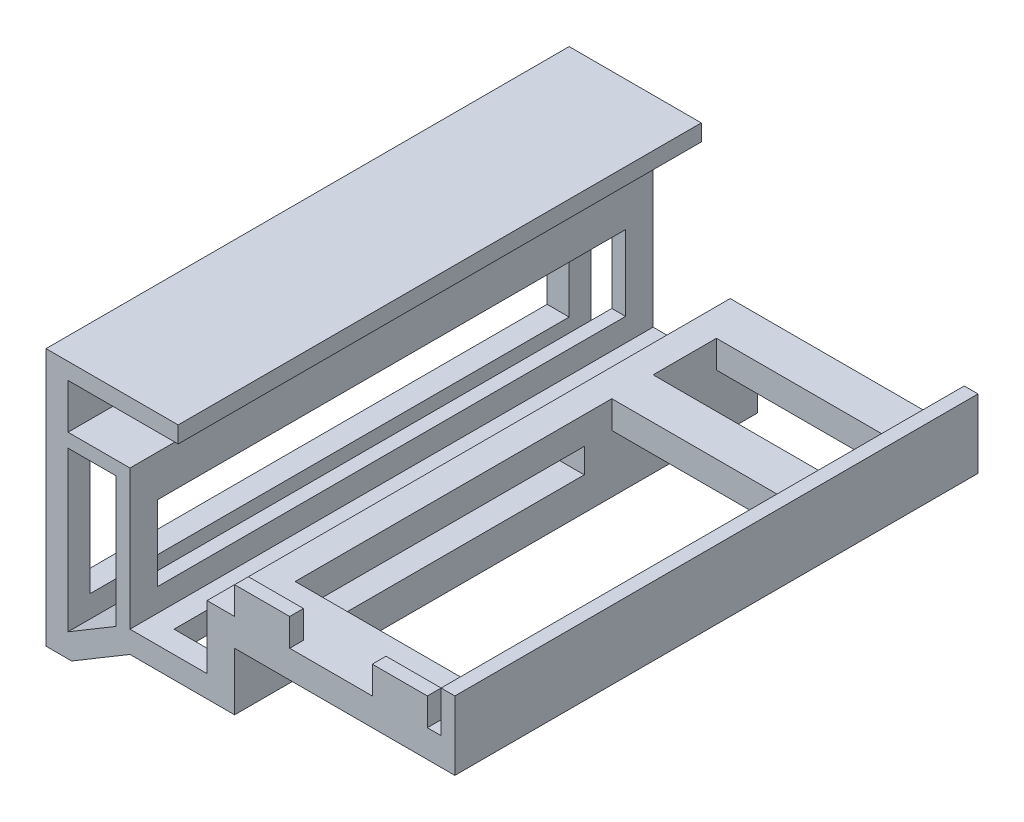
SolidWorks part; units mm, degrees
ref_plane "前视基准面" through (0, 0, 0) normal (0, 0, 1) x (1, 0, 0)
ref_plane "上视基准面" through (0, 0, 0) normal (0, 1, 0) x (1, 0, 0)
ref_plane "右视基准面" through (0, 0, 0) normal (1, 0, 0) x (0, 0, -1)
other "Configuration Table"
sketch "草图1" plane through (0, 0, 0) normal (0, 0, 1) x (1, 0, 0)
  line L0 (0, 0) -> (-22.5, 0)
  line L1 (-22.5, 0) -> (-22.5, 16.3)
  line L2 (-22.5, 16.3) -> (17.5, 16.3)
  line L3 (17.5, 16.3) -> (17.5, 22.3)
  line L4 (17.5, 22.3) -> (-30.5, 22.3)
  line L5 (-30.5, 22.3) -> (-30.5, -71.3085)
  line L6 (-30.5, -71.3085) -> (-21.1866, -71.3085)
  line L14 (113, -27.7) -> (28, -27.7)
  line L15 (28, -27.7) -> (28, -50.7)
  line L16 (28, -50.7) -> (0, -50.7)
  line L17 (0, -50.7) -> (0, 0)
  line L21 (118, -37.7) -> (38, -37.7)
  line L22 (38, -37.7) -> (38, -58.6513)
  line L23 (38, -58.6513) -> (0, -58.6513)
  line L24 (0, -58.6513) -> (-21.1866, -71.3085)
  line L26 (118, -37.7) -> (118, -12.7)
  line L27 (118, -12.7) -> (113, -12.7)
  line L28 (113, -12.7) -> (113, -27.7)
  dimension "D1" = 8
  dimension "D2" = 6
  dimension "D3" = 40
  dimension "D4" = 16.3
  dimension "D5" = 28
  dimension "D6" = 22.5
  dimension "D7" = 50.7
  dimension "D8" = 23
  dimension "D9" = 10
  dimension "D10" = 10
  dimension "D11" = 85
  dimension "D12" = 5
  dimension "D13" = 25
extrude "凸台-拉伸1" add sketch "草图1" along normal blind 190 contours L5 L6 L24 L23 L22 L21 L26 L27 L28 L14 L15 L16 L17 L0 L1 L2 L3 L4
sketch "草图2" plane through (0, 0, 190) normal (0, 0, 1) x (1, 0, 0)
  line L0 (-22.5, -5) -> (-22.5, -62.7742)
  line L1 (-22.5, -62.7742) -> (-5, -52.3194)
  line L2 (-5, -52.3194) -> (-5, -5)
  line L3 (-5, -5) -> (-22.5, -5)
  line L18 (17.5, 22.3) -> (-30.5, 22.3)
  line L19 (-30.5, 22.3) -> (-30.5, -71.3085)
  line L20 (-30.5, -71.3085) -> (-21.1866, -71.3085)
  line L21 (-21.1866, -71.3085) -> (0, -58.6513)
  line L22 (0, -58.6513) -> (38, -58.6513)
  line L23 (38, -58.6513) -> (38, -37.7)
  line L24 (38, -37.7) -> (118, -37.7)
  line L25 (118, -37.7) -> (118, -12.7)
  line L26 (118, -12.7) -> (113, -12.7)
  line L27 (113, -12.7) -> (113, -27.7)
  line L28 (113, -27.7) -> (28, -27.7)
  line L29 (28, -27.7) -> (28, -50.7)
  line L30 (28, -50.7) -> (0, -50.7)
  line L31 (0, -50.7) -> (0, 0)
  line L32 (0, 0) -> (-22.5, 0)
  line L33 (-22.5, 0) -> (-22.5, 16.3)
  line L34 (-22.5, 16.3) -> (17.5, 16.3)
  line L35 (17.5, 16.3) -> (17.5, 22.3)
  line L36 (17.5, 22.3) -> (-30.5, 22.3) construction
  line L37 (-30.5, 22.3) -> (-30.5, -71.3085) construction
  line L38 (-30.5, -71.3085) -> (-21.1866, -71.3085) construction
  line L39 (-21.1866, -71.3085) -> (0, -58.6513) construction
  line L40 (0, -58.6513) -> (38, -58.6513) construction
  line L41 (38, -58.6513) -> (38, -37.7) construction
  line L42 (38, -37.7) -> (118, -37.7) construction
  line L43 (118, -37.7) -> (118, -12.7) construction
  line L44 (118, -12.7) -> (113, -12.7) construction
  line L45 (113, -12.7) -> (113, -27.7) construction
  line L46 (113, -27.7) -> (28, -27.7) construction
  line L47 (28, -27.7) -> (28, -50.7) construction
  line L48 (28, -50.7) -> (0, -50.7) construction
  line L49 (0, -50.7) -> (0, 0) construction
  line L50 (0, 0) -> (-22.5, 0) construction
  line L51 (-22.5, 0) -> (-22.5, 16.3) construction
  line L52 (-22.5, 16.3) -> (17.5, 16.3) construction
  line L53 (17.5, 16.3) -> (17.5, 22.3) construction
  point P6 (-11.25, 0)
  dimension "D2" = 8
  dimension "D3" = 5
  dimension "D4" = 5
  dimension "D5" = 8
  dimension "D1" = 0
extrude "切除-拉伸1" cut sketch "草图2" against normal through all contours L3 L0 L1 L2
sketch "草图4" plane through (0, -27.7, 0) normal (0, 1, 0) x (1, 0, 0)
  line L0 (38, -15) -> (113, -15)
  line L1 (113, -15) -> (113, -38)
  line L2 (113, -38) -> (38, -38)
  line L4 (113, 0) -> (28, 0)
  line L5 (28, 0) -> (28, -190)
  line L6 (28, -190) -> (113, -190)
  line L7 (113, -190) -> (113, 0)
  line L8 (113, 0) -> (28, 0) construction
  line L9 (28, 0) -> (28, -190) construction
  line L10 (28, -190) -> (113, -190) construction
  line L11 (113, -190) -> (113, 0) construction
  line L12 (38, -190) -> (38, 0) construction
  line L13 (38, -190) -> (38, 0) construction
  line L14 (38, -15) -> (38, -38)
  dimension "D2" = 15
  dimension "D3" = 23
  dimension "D1" = 0
extrude "切除-拉伸2" cut sketch "草图4" against normal through all contours L0 L1 L2 L14
sketch "草图6" plane through (0, -27.7, 0) normal (0, 1, 0) x (1, 0, 0)
  line L0 (38, -53) -> (38, -168)
  line L1 (38, -168) -> (113, -168)
  line L2 (113, -168) -> (113, -53)
  line L3 (113, -53) -> (38, -53)
  line L8 (38, -15) -> (113, -15)
  line L9 (113, -15) -> (113, 0)
  line L10 (113, 0) -> (28, 0)
  line L11 (28, 0) -> (28, -190)
  line L12 (28, -190) -> (113, -190)
  line L13 (113, -190) -> (113, -38)
  line L14 (113, -38) -> (38, -38)
  line L15 (38, -38) -> (38, -15)
  line L16 (38, -15) -> (113, -15) construction
  line L17 (113, -15) -> (113, 0) construction
  line L18 (113, 0) -> (28, 0) construction
  line L19 (28, 0) -> (28, -190) construction
  line L20 (28, -190) -> (113, -190) construction
  line L21 (113, -190) -> (113, -38) construction
  line L22 (113, -38) -> (38, -38) construction
  line L23 (38, -38) -> (38, -15) construction
  dimension "D2" = 15
  dimension "D3" = 115
  dimension "D1" = 0
extrude "切除-拉伸3" cut sketch "草图6" against normal through all
sketch "草图7" plane through (0, -27.7, 0) normal (0, 1, 0) x (1, 0, 0)
  line L2 (38, -190) -> (58, -190)
  line L3 (38, -190) -> (38, -185)
  line L4 (38, -185) -> (58, -185)
  line L5 (58, -190) -> (58, -185)
  point P0 (0, 0)
  dimension "D1" = 5
  dimension "D2" = 20
extrude "凸台-拉伸3" add sketch "草图7" along normal blind 10 contours L4 L5 L2 L3
pattern_linear "阵列(线性)1" count 2 spacing 50 along (1, 0, 0) of "凸台-拉伸3"
sketch "草图8" plane through (38, 0, 0) normal (1, 0, 0) x (0, 0, -1)
  line L4 (-63, -46.6513) -> (-63, -37.7)
  line L5 (-63, -37.7) -> (-158, -37.7)
  line L6 (-158, -37.7) -> (-158, -46.6513)
  line L8 (-158, -46.6513) -> (-63, -46.6513)
  line L12 (-190, -58.6513) -> (0, -58.6513)
  line L13 (0, -58.6513) -> (0, -37.7)
  line L14 (0, -37.7) -> (-15, -37.7)
  line L15 (-15, -37.7) -> (-15, -27.7)
  line L16 (-15, -27.7) -> (-38, -27.7)
  line L17 (-38, -27.7) -> (-38, -37.7)
  line L18 (-38, -37.7) -> (-53, -37.7)
  line L19 (-53, -37.7) -> (-53, -27.7)
  line L20 (-53, -27.7) -> (-168, -27.7)
  line L21 (-168, -27.7) -> (-168, -37.7)
  line L22 (-168, -37.7) -> (-190, -37.7)
  line L23 (-190, -37.7) -> (-190, -58.6513)
  line L24 (-190, -58.6513) -> (0, -58.6513) construction
  line L25 (0, -58.6513) -> (0, -37.7) construction
  line L26 (0, -37.7) -> (-15, -37.7) construction
  line L27 (-15, -37.7) -> (-15, -27.7) construction
  line L28 (-15, -27.7) -> (-38, -27.7) construction
  line L29 (-38, -27.7) -> (-38, -37.7) construction
  line L30 (-38, -37.7) -> (-53, -37.7) construction
  line L31 (-53, -37.7) -> (-53, -27.7) construction
  line L32 (-53, -27.7) -> (-168, -27.7) construction
  line L33 (-168, -27.7) -> (-168, -37.7) construction
  line L34 (-168, -37.7) -> (-190, -37.7) construction
  line L35 (-190, -37.7) -> (-190, -58.6513) construction
  point P10 (-53, -32.7)
  dimension "D2" = 10
  dimension "D3" = 10
  dimension "D4" = 12
  dimension "D1" = 0
extrude "切除-拉伸4" cut sketch "草图8" against normal up to next contours L8 L4 L5 L6
sketch "草图9" plane through (0, -50.7, 0) normal (0, 1, 0) x (1, 0, 0)
  line L8 (20, -8) -> (8, -8)
  line L9 (8, -8) -> (8, -182)
  line L10 (8, -182) -> (20, -182)
  line L11 (20, -182) -> (20, -8)
  line L12 (20, -8) -> (8, -8)
  line L13 (8, -8) -> (8, -182)
  line L14 (8, -182) -> (20, -182)
  line L15 (20, -182) -> (20, -8)
  dimension "D1" = 8
extrude "切除-拉伸5" cut sketch "草图9" against normal up to next
sketch "草图10" plane through (-5, 0, 0) normal (-1, 0, 0) x (0, 0, 1)
  line L8 (180, -42.3194) -> (180, -15)
  line L9 (180, -15) -> (10, -15)
  line L10 (10, -15) -> (10, -42.3194)
  line L11 (10, -42.3194) -> (180, -42.3194)
  line L12 (180, -42.3194) -> (180, -15)
  line L13 (180, -15) -> (10, -15)
  line L14 (10, -15) -> (10, -42.3194)
  line L15 (10, -42.3194) -> (180, -42.3194)
  dimension "D1" = 10
extrude "切除-拉伸6" cut sketch "草图10" against normal up to next
sketch "草图12" plane through (-22.5, 0, 0) normal (1, 0, 0) x (0, 0, -1)
  line L8 (-182, -13) -> (-182, -54.7742)
  line L9 (-182, -54.7742) -> (-8, -54.7742)
  line L10 (-8, -54.7742) -> (-8, -13)
  line L11 (-8, -13) -> (-182, -13)
  line L12 (-182, -13) -> (-182, -54.7742)
  line L13 (-182, -54.7742) -> (-8, -54.7742)
  line L14 (-8, -54.7742) -> (-8, -13)
  line L15 (-8, -13) -> (-182, -13)
  dimension "D1" = 8
extrude "切除-拉伸7" cut sketch "草图12" against normal up to next
